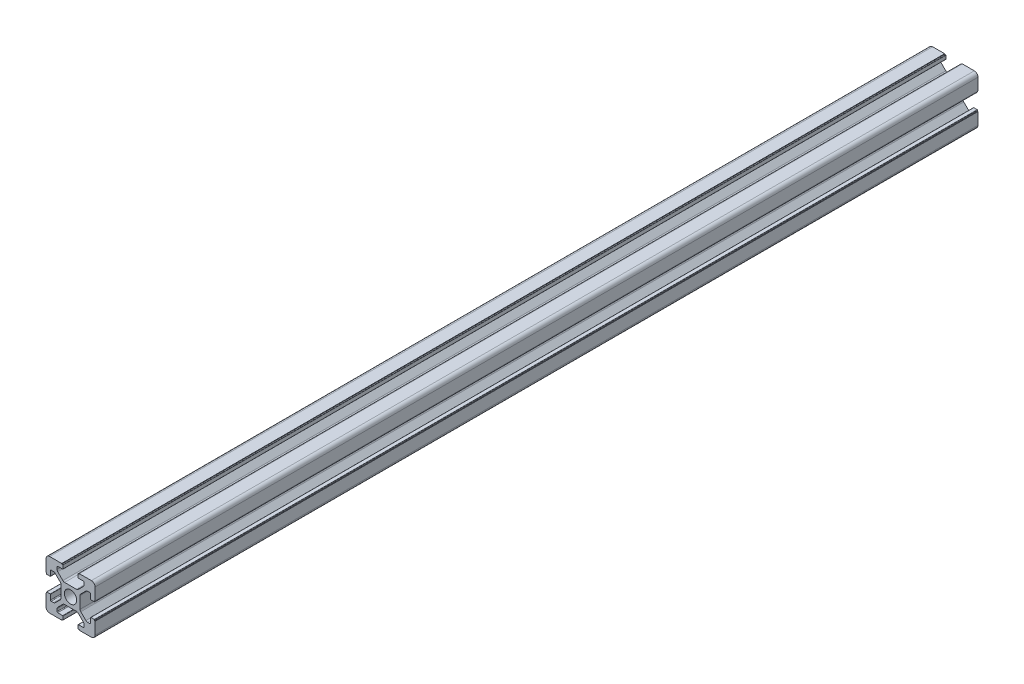
SolidWorks part; units mm, degrees
material "6063-T5"
ref_plane "前视基准面" through (0, 0, 0) normal (0, 0, 1) x (1, 0, 0)
ref_plane "上视基准面" through (0, 0, 0) normal (0, 1, 0) x (1, 0, 0)
ref_plane "右视基准面" through (0, 0, 0) normal (1, 0, 0) x (0, 0, -1)
sketch "草图1" plane through (0, 0, 0) normal (0, 0, 1) x (1, 0, 0)
  line L0 (-1.4389, 10) -> (24.3741, 10) construction
  line L1 (20, 13.6) -> (20, 20)
  line L2 (0, 0) -> (0, 6.4)
  line L3 (0, 20) -> (6.4, 20)
  line L4 (20, 0) -> (20, 6.4)
  line L5 (10, 21.5388) -> (10, -2.4017) construction
  line L6 (6.9, 18.3) -> (6.9, 19.7)
  line L7 (6.8, 18.2) -> (4.8, 18.2)
  line L8 (4.5, 17.9) -> (4.5, 16.9749)
  line L9 (4.7929, 16.2678) -> (6.8678, 14.1929)
  line L10 (7.5749, 13.9) -> (12.4251, 13.9)
  line L11 (6.8, 19.8) -> (6.4, 19.8)
  line L12 (6.4, 19.8) -> (6.4, 20)
  line L13 (0, 13.6) -> (0.2, 13.6)
  line L14 (0.2, 13.6) -> (0.2, 13.2)
  line L15 (0.3, 13.1) -> (1.7, 13.1)
  line L16 (1.8, 13.2) -> (1.8, 15.2)
  line L17 (2.1, 15.5) -> (3.0251, 15.5)
  line L18 (3.7322, 15.2071) -> (5.8071, 13.1322)
  line L19 (6.1, 12.4251) -> (6.1, 7.5749)
  line L20 (13.6, 19.8) -> (13.6, 20)
  line L21 (13.2, 19.8) -> (13.6, 19.8)
  line L22 (13.1, 18.3) -> (13.1, 19.7)
  line L23 (13.2, 18.2) -> (15.2, 18.2)
  line L24 (15.5, 17.9) -> (15.5, 16.9749)
  line L25 (15.2071, 16.2678) -> (13.1322, 14.1929)
  line L26 (0, 6.4) -> (0.2, 6.4)
  line L27 (0.2, 6.4) -> (0.2, 6.8)
  line L28 (0.3, 6.9) -> (1.7, 6.9)
  line L29 (1.8, 6.8) -> (1.8, 4.8)
  line L30 (2.1, 4.5) -> (3.0251, 4.5)
  line L31 (3.7322, 4.7929) -> (5.8071, 6.8678)
  line L32 (13.6, 20) -> (20, 20)
  line L33 (0, 13.6) -> (0, 20)
  line L34 (13.6, 0.2) -> (13.6, 0)
  line L35 (13.2, 0.2) -> (13.6, 0.2)
  line L36 (13.1, 1.7) -> (13.1, 0.3)
  line L37 (13.2, 1.8) -> (15.2, 1.8)
  line L38 (15.5, 2.1) -> (15.5, 3.0251)
  line L39 (15.2071, 3.7322) -> (13.1322, 5.8071)
  line L40 (4.5, 2.1) -> (4.5, 3.0251)
  line L41 (6.8, 1.8) -> (4.8, 1.8)
  line L42 (6.4, 0.2) -> (6.4, 0)
  line L43 (6.8, 0.2) -> (6.4, 0.2)
  line L44 (6.9, 1.7) -> (6.9, 0.3)
  line L45 (4.7929, 3.7322) -> (6.8678, 5.8071)
  line L46 (7.5749, 6.1) -> (12.4251, 6.1)
  line L47 (20, 6.4) -> (19.8, 6.4)
  line L48 (19.8, 6.4) -> (19.8, 6.8)
  line L49 (19.7, 6.9) -> (18.3, 6.9)
  line L50 (18.2, 6.8) -> (18.2, 4.8)
  line L51 (17.9, 4.5) -> (16.9749, 4.5)
  line L52 (16.2678, 4.7929) -> (14.1929, 6.8678)
  line L53 (13.9, 12.4251) -> (13.9, 7.5749)
  line L54 (16.2678, 15.2071) -> (14.1929, 13.1322)
  line L55 (17.9, 15.5) -> (16.9749, 15.5)
  line L56 (18.2, 13.2) -> (18.2, 15.2)
  line L57 (19.7, 13.1) -> (18.3, 13.1)
  line L58 (19.8, 13.6) -> (19.8, 13.2)
  line L59 (20, 13.6) -> (19.8, 13.6)
  line L60 (0, 0) -> (6.4, 0)
  line L61 (13.6, 0) -> (20, 0)
  arc A0 (6.1, 12.4251) -> (5.8071, 13.1322) centre (5.1, 12.4251) ccw
  arc A1 (7.5749, 13.9) -> (6.8678, 14.1929) centre (7.5749, 14.9) cw
  arc A2 (4.5, 16.9749) -> (4.7929, 16.2678) centre (5.5, 16.9749) ccw
  arc A3 (3.7322, 15.2071) -> (3.0251, 15.5) centre (3.0251, 14.5) ccw
  arc A4 (4.5, 17.9) -> (4.8, 18.2) centre (4.8, 17.9) cw
  arc A5 (1.8, 15.2) -> (2.1, 15.5) centre (2.1, 15.2) cw
  arc A6 (0.3, 13.1) -> (0.2, 13.2) centre (0.3, 13.2) cw
  arc A7 (6.9, 19.7) -> (6.8, 19.8) centre (6.8, 19.7) ccw
  arc A8 (1.7, 13.1) -> (1.8, 13.2) centre (1.7, 13.2) ccw
  arc A9 (6.9, 18.3) -> (6.8, 18.2) centre (6.8, 18.3) cw
  arc A10 (13.1, 19.7) -> (13.2, 19.8) centre (13.2, 19.7) cw
  arc A11 (13.1, 18.3) -> (13.2, 18.2) centre (13.2, 18.3) ccw
  arc A12 (15.5, 17.9) -> (15.2, 18.2) centre (15.2, 17.9) ccw
  arc A13 (15.5, 16.9749) -> (15.2071, 16.2678) centre (14.5, 16.9749) cw
  arc A14 (12.4251, 13.9) -> (13.1322, 14.1929) centre (12.4251, 14.9) ccw
  arc A15 (0.3, 6.9) -> (0.2, 6.8) centre (0.3, 6.8) ccw
  arc A16 (1.7, 6.9) -> (1.8, 6.8) centre (1.7, 6.8) cw
  arc A17 (1.8, 4.8) -> (2.1, 4.5) centre (2.1, 4.8) ccw
  arc A18 (3.7322, 4.7929) -> (3.0251, 4.5) centre (3.0251, 5.5) cw
  arc A19 (6.1, 7.5749) -> (5.8071, 6.8678) centre (5.1, 7.5749) cw
  arc A20 (13.1, 0.3) -> (13.2, 0.2) centre (13.2, 0.3) ccw
  arc A21 (13.1, 1.7) -> (13.2, 1.8) centre (13.2, 1.7) cw
  arc A22 (15.5, 2.1) -> (15.2, 1.8) centre (15.2, 2.1) cw
  arc A23 (15.5, 3.0251) -> (15.2071, 3.7322) centre (14.5, 3.0251) ccw
  arc A24 (12.4251, 6.1) -> (13.1322, 5.8071) centre (12.4251, 5.1) cw
  arc A25 (4.5, 2.1) -> (4.8, 1.8) centre (4.8, 2.1) ccw
  arc A26 (6.9, 0.3) -> (6.8, 0.2) centre (6.8, 0.3) cw
  arc A27 (6.9, 1.7) -> (6.8, 1.8) centre (6.8, 1.7) ccw
  arc A28 (4.5, 3.0251) -> (4.7929, 3.7322) centre (5.5, 3.0251) cw
  arc A29 (7.5749, 6.1) -> (6.8678, 5.8071) centre (7.5749, 5.1) ccw
  arc A30 (19.7, 6.9) -> (19.8, 6.8) centre (19.7, 6.8) cw
  arc A31 (18.3, 6.9) -> (18.2, 6.8) centre (18.3, 6.8) ccw
  arc A32 (18.2, 4.8) -> (17.9, 4.5) centre (17.9, 4.8) cw
  arc A33 (16.2678, 4.7929) -> (16.9749, 4.5) centre (16.9749, 5.5) ccw
  arc A34 (13.9, 7.5749) -> (14.1929, 6.8678) centre (14.9, 7.5749) ccw
  arc A35 (13.9, 12.4251) -> (14.1929, 13.1322) centre (14.9, 12.4251) cw
  arc A36 (16.2678, 15.2071) -> (16.9749, 15.5) centre (16.9749, 14.5) cw
  arc A37 (18.2, 15.2) -> (17.9, 15.5) centre (17.9, 15.2) ccw
  arc A38 (18.3, 13.1) -> (18.2, 13.2) centre (18.3, 13.2) cw
  arc A39 (19.7, 13.1) -> (19.8, 13.2) centre (19.7, 13.2) ccw
  circle A40 centre (10, 10) radius 2.5
  point P39 (0.2, 13.1)
  point P42 (6.9, 19.8)
  point P45 (1.8, 13.1)
  point P48 (6.9, 18.2)
  point P66 (10, 13.9)
  point P83 (6.1, 10)
  dimension "D19" = 1
  dimension "D20" = 1
  dimension "D21" = 0.3
  dimension "D22" = 0.1
  dimension "D23" = 5
  dimension "D1" = 20
  dimension "D2" = 20
  dimension "D3" = 10
  dimension "D4" = 10
  dimension "D5" = 1.8
  dimension "D6" = 0.5
  dimension "D7" = 1.6
  dimension "D8" = 3.1
  dimension "D9" = 6.1
  dimension "D10" = 5.5
  dimension "D11" = 3.1
  dimension "D12" = 6.1
  dimension "D13" = 5.5
  dimension "D14" = 1.8
  dimension "D15" = 0.5
  dimension "D16" = 1.5
  dimension "D17" = 45
  dimension "D18" = 1.6
extrude "凸台-拉伸1" add sketch "草图1" along normal blind 360
fillet "圆角1" radius 1.5 4 edges at (20, 0, 180) (0, 0, 180) (0, 20, 180) (20, 20, 180)
